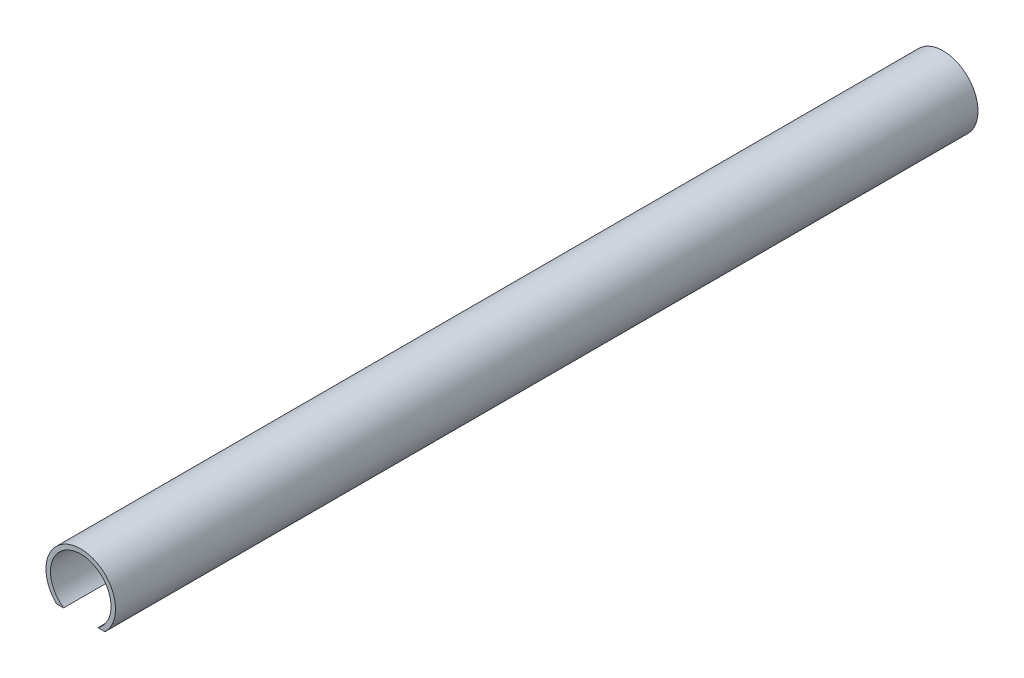
SolidWorks part; units mm, degrees
material "PVC Rigid"
ref_plane "Front Plane" through (0, 0, 0) normal (0, 0, 1) x (1, 0, 0)
ref_plane "Top Plane" through (0, 0, 0) normal (0, 1, 0) x (1, 0, 0)
ref_plane "Right Plane" through (0, 0, 0) normal (1, 0, 0) x (0, 0, -1)
sketch "Sketch1" plane through (0, 0, 0) normal (0, 0, 1) x (1, 0, 0)
  circle A0 centre (0, 0) radius 26.2509
  circle A1 centre (0, 0) radius 30.1625
  dimension "D1" = 60.325
  dimension "D2" = 3.9116
extrude "Boss-Extrude1" add sketch "Sketch1" along normal up to surface (747.9032 mm away)
sketch "Sketch2" plane through (0, 0, 0) normal (1, 0, 0) x (0, 0, -1)
  line L0 (-732.0282, -21.6484) -> (-687.5782, -21.6484)
  line L1 (-728.8532, -24.8234) -> (-690.7532, -24.8234) construction
  line L2 (-728.8532, -24.8234) -> (-728.8532, -37.5234) construction
  line L3 (-728.8532, -37.5234) -> (-690.7532, -37.5234) construction
  line L4 (-690.7532, -24.8234) -> (-690.7532, -37.5234) construction
  line L5 (-518.7032, -37.5234) -> (-467.9032, -37.5234) construction
  line L6 (-518.7032, -37.5234) -> (-518.7032, -24.8234) construction
  line L7 (-518.7032, -24.8234) -> (-467.9032, -24.8234) construction
  line L8 (-467.9032, -37.5234) -> (-467.9032, -24.8234) construction
  line L9 (-687.5782, -21.6484) -> (-687.5782, -40.6984)
  line L10 (-732.0282, -40.6984) -> (-687.5782, -40.6984)
  line L11 (-732.0282, -21.6484) -> (-732.0282, -40.6984) construction
  line L12 (-521.8782, -40.6984) -> (-464.7282, -40.6984)
  line L13 (-464.7282, -40.6984) -> (-464.7282, -21.6484)
  line L14 (-521.8782, -21.6484) -> (-464.7282, -21.6484)
  line L15 (-521.8782, -40.6984) -> (-521.8782, -21.6484)
  line L16 (-732.0282, -21.6484) -> (-757.6967, -21.6484)
  line L17 (-757.6967, -21.6484) -> (-757.6967, -40.6984)
  line L18 (-757.6967, -40.6984) -> (-732.0282, -40.6984)
  dimension "D1" = 3.175
extrude "Cut-Extrude1" cut sketch "Sketch2" against normal through all both and the other way through all contours L0 L9 L10 L18 L17 L16 | L14 L13 L12 L15
